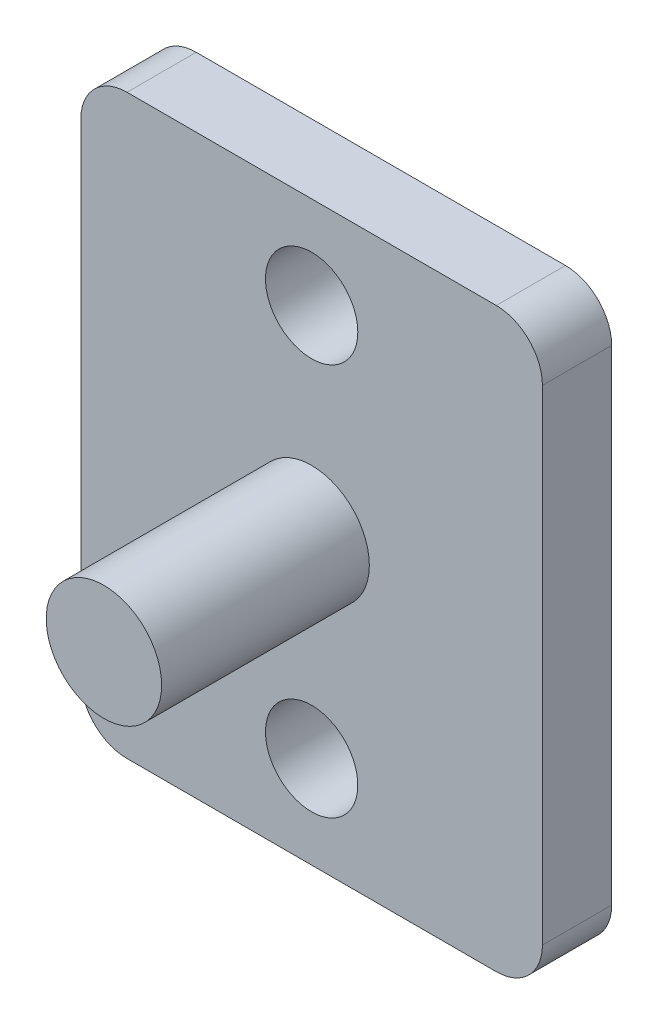
SolidWorks part; units mm, degrees
ref_plane "Plan de face" through (0, 0, 0) normal (0, 0, 1) x (1, 0, 0)
ref_plane "Plan de dessus" through (0, 0, 0) normal (0, 1, 0) x (1, 0, 0)
ref_plane "Plan de droite" through (0, 0, 0) normal (1, 0, 0) x (0, 0, -1)
sketch "Esquisse1" plane through (0, 0, 0) normal (0, 0, 1) x (1, 0, 0)
  line L0 (-15.1236, 0) -> (14.6728, 0) construction
  line L1 (10, -12.5) -> (-10, -12.5)
  line L2 (10, -12.5) -> (10, 12.5)
  line L3 (10, 12.5) -> (-10, 12.5)
  line L4 (-10, -12.5) -> (-10, 12.5)
  line L5 (10, -12.5) -> (-10, 12.5) construction
  line L6 (10, 12.5) -> (-10, -12.5) construction
  circle A0 centre (0, 8.5) radius 2
  circle A1 centre (0, -8.5) radius 2
  point P0 (0, 0)
  dimension "D3" = 4
  dimension "D1" = 20
  dimension "D2" = 25
  dimension "D4" = 4
extrude "Boss.-Extru.1" add sketch "Esquisse1" along normal blind 3
sketch "Esquisse2" plane through (0, 0, 3) normal (0, 0, 1) x (1, 0, 0)
  circle A0 centre (0, 0) radius 2.5
  dimension "D1" = 5
fillet "Congé1" radius 2 4 edges at (-10, -12.5, 1.5) (10, -12.5, 1.5) (10, 12.5, 1.5) (-10, 12.5, 1.5)
extrude "Boss.-Extru.3" add sketch "Esquisse2" along normal blind 9
